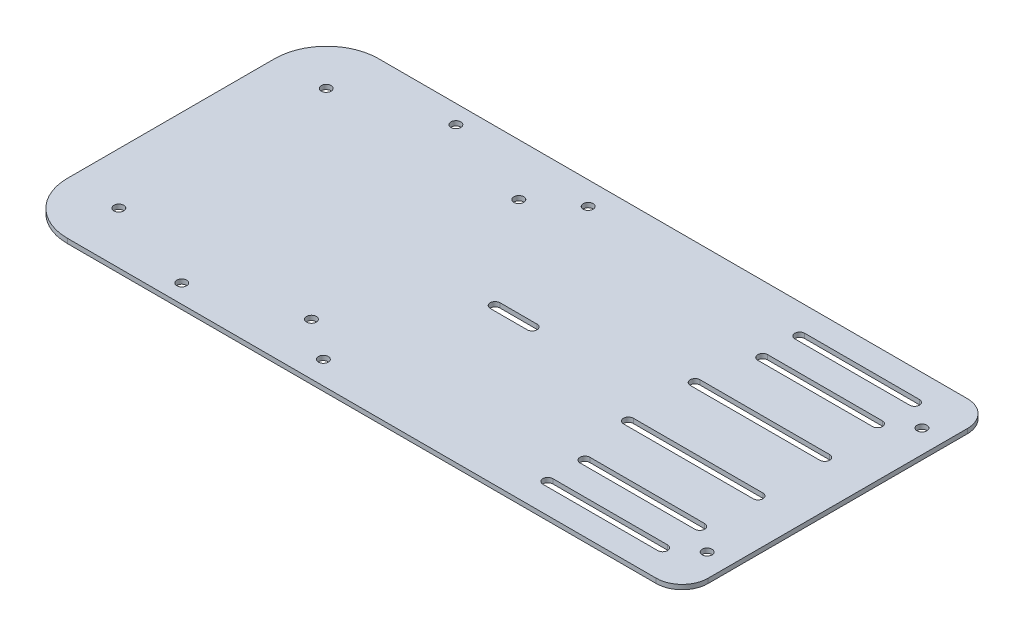
SolidWorks part; units mm, degrees
material "Thornel Mat VMA"
ref_plane "Front Plane" through (0, 0, 0) normal (0, 0, 1) x (1, 0, 0)
ref_plane "Top Plane" through (0, 0, 0) normal (0, 1, 0) x (1, 0, 0)
ref_plane "Right Plane" through (0, 0, 0) normal (1, 0, 0) x (0, 0, -1)
sketch "Sketch1" plane through (0, 0, 0) normal (0, 1, 0) x (1, 0, 0)
  line L0 (-129.54, 0) -> (152.4, 0) construction
  line L1 (-240.157, 106.68) -> (240.157, 106.68)
  line L2 (-240.157, 106.68) -> (-240.157, -106.68)
  line L3 (-240.157, -106.68) -> (240.157, -106.68)
  line L4 (240.157, 106.68) -> (240.157, -73.66)
  line L5 (-240.157, 106.68) -> (240.157, -106.68) construction
  line L6 (-240.157, -106.68) -> (240.157, 106.68) construction
  line L7 (119.507, -22.86) -> (208.407, -22.86) construction
  line L8 (119.507, -19.4818) -> (208.407, -19.4818)
  line L9 (119.507, -26.2382) -> (208.407, -26.2382)
  line L10 (119.507, 22.86) -> (208.407, 22.86) construction
  line L11 (119.507, 19.4818) -> (208.407, 19.4818)
  line L12 (119.507, 26.2382) -> (208.407, 26.2382)
  line L13 (127.762, -60.96) -> (206.502, -60.96) construction
  line L14 (127.762, -57.5818) -> (206.502, -57.5818)
  line L15 (127.762, -64.3382) -> (206.502, -64.3382)
  line L16 (240.157, -73.66) -> (240.157, -106.68)
  line L17 (240.157, -73.66) -> (-240.157, -73.66) construction
  line L18 (127.762, -86.36) -> (206.502, -86.36) construction
  line L19 (127.762, -89.7382) -> (206.502, -89.7382)
  line L20 (127.762, -82.9818) -> (206.502, -82.9818)
  line L21 (127.762, 60.96) -> (206.502, 60.96) construction
  line L22 (127.762, 57.5818) -> (206.502, 57.5818)
  line L23 (127.762, 64.3382) -> (206.502, 64.3382)
  line L24 (127.762, 86.36) -> (206.502, 86.36) construction
  line L25 (127.762, 89.7382) -> (206.502, 89.7382)
  line L26 (127.762, 82.9818) -> (206.502, 82.9818)
  line L27 (5.207, 0) -> (30.607, 0) construction
  line L28 (5.207, 3.3782) -> (30.607, 3.3782)
  line L29 (5.207, -3.3782) -> (30.607, -3.3782)
  arc A0 (119.507, -19.4818) -> (119.507, -26.2382) centre (119.507, -22.86) ccw
  arc A1 (208.407, -26.2382) -> (208.407, -19.4818) centre (208.407, -22.86) ccw
  arc A2 (119.507, 19.4818) -> (119.507, 26.2382) centre (119.507, 22.86) cw
  arc A3 (208.407, 26.2382) -> (208.407, 19.4818) centre (208.407, 22.86) cw
  circle A4 centre (224.282, -73.66) radius 3.3782
  arc A5 (127.762, -57.5818) -> (127.762, -64.3382) centre (127.762, -60.96) ccw
  arc A6 (206.502, -64.3382) -> (206.502, -57.5818) centre (206.502, -60.96) ccw
  arc A7 (127.762, -89.7382) -> (127.762, -82.9818) centre (127.762, -86.36) cw
  arc A8 (206.502, -82.9818) -> (206.502, -89.7382) centre (206.502, -86.36) cw
  circle A9 centre (-21.7805, -90.805) radius 3.3782
  circle A10 centre (-21.7805, 90.805) radius 3.3782
  arc A11 (127.762, 57.5818) -> (127.762, 64.3382) centre (127.762, 60.96) cw
  arc A12 (206.502, 64.3382) -> (206.502, 57.5818) centre (206.502, 60.96) cw
  arc A13 (127.762, 89.7382) -> (127.762, 82.9818) centre (127.762, 86.36) ccw
  arc A14 (206.502, 82.9818) -> (206.502, 89.7382) centre (206.502, 86.36) ccw
  circle A15 centre (224.282, 73.66) radius 3.3782
  arc A16 (5.207, 3.3782) -> (5.207, -3.3782) centre (5.207, 0) ccw
  arc A17 (30.607, -3.3782) -> (30.607, 3.3782) centre (30.607, 0) ccw
  circle A18 centre (-115.697, 93.98) radius 3.3782
  circle A19 centre (-115.697, -93.98) radius 3.3782
  circle A20 centre (-181.737, 71.12) radius 3.3782
  circle A21 centre (-49.657, 71.12) radius 3.3782
  circle A22 centre (-49.657, -71.12) radius 3.3782
  circle A23 centre (-181.737, -71.12) radius 3.3782
  point P0 (0, 0)
  point P10 (163.957, -22.86)
  point P17 (163.957, 22.86)
  point P25 (167.132, -60.96)
  point P35 (167.132, -86.36)
  point P46 (167.132, 60.96)
  point P53 (167.132, 86.36)
  point P62 (17.907, 0)
  point P77 (-181.737, -71.12)
  dimension "D5" = 3.3782
  dimension "D10" = 6.7564
  dimension "D18" = 6.7564
  dimension "D17" = 3.3782
  dimension "D20" = 71.12
  dimension "D22" = 6.7564
  dimension "D23" = 6.7564
  dimension "D2" = 213.36
  dimension "D3" = 22.86
  dimension "D4" = 31.75
  dimension "D6" = 88.9
  dimension "D7" = 33.02
  dimension "D8" = 17.78
  dimension "D9" = 12.7
  dimension "D11" = 15.875
  dimension "D12" = 78.74
  dimension "D13" = 261.9375
  dimension "D14" = 15.875
  dimension "D15" = 25.4
  dimension "D16" = 209.55
  dimension "D19" = 480.314
  dimension "D21" = 58.42
  dimension "D24" = 132.08
  dimension "D25" = 71.12
  dimension "D26" = 12.7
  dimension "D27" = 66.04
extrude "Boss-Extrude1" add sketch "Sketch1" along normal blind 3.175
sketch "Sketch4" plane through (0, 3.175, 0) normal (0, 1, 0) x (1, 0, 0)
  line L0 (-240.157, -106.68) -> (240.157, -106.68) construction
  line L1 (-240.157, 106.68) -> (-217.043, 106.68)
  line L2 (-240.157, 106.68) -> (-240.157, -106.68)
  line L3 (-240.157, -106.68) -> (-217.043, -106.68)
  line L4 (-217.043, 106.68) -> (-217.043, -106.68)
  dimension "D1" = 23.114
extrude "Cut-Extrude1" cut sketch "Sketch4" against normal through all
fillet "Fillet1" radius 17.78 2 edges at (240.157, 1.5875, -106.68) (240.157, 1.5875, 106.68)
fillet "Fillet2" radius 35.56 2 edges at (-217.043, 1.5875, 106.68) (-217.043, 1.5875, -106.68)
